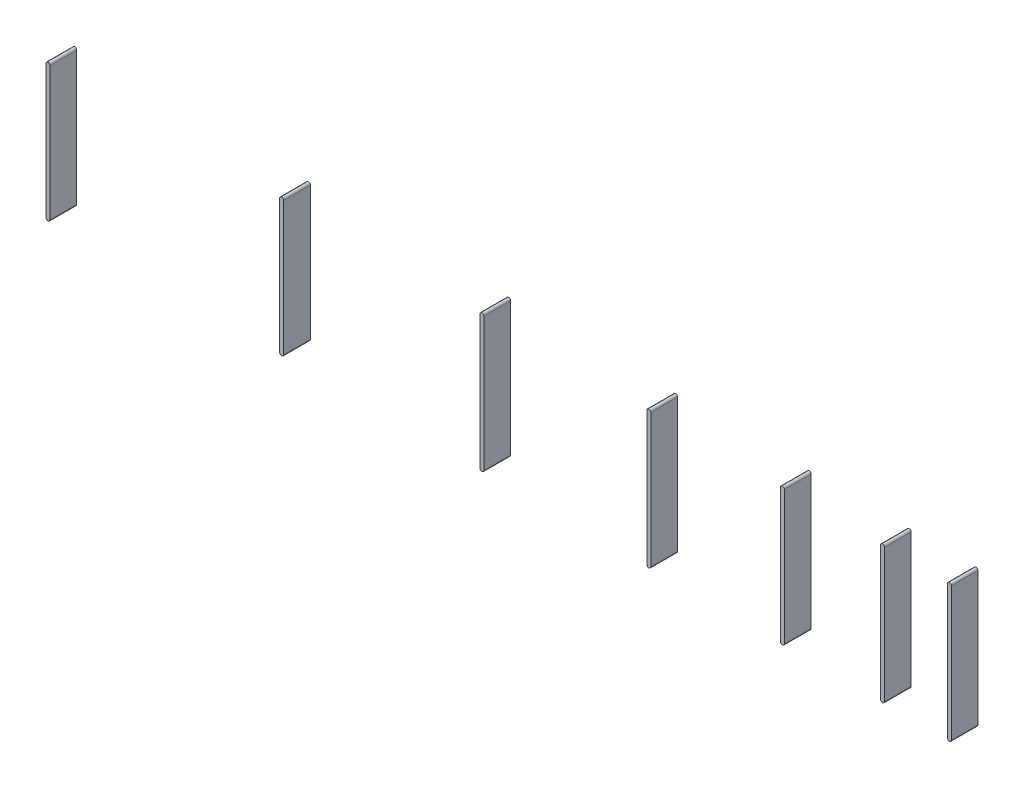
SolidWorks part; units mm, degrees
ref_plane "Front Plane" through (0, 0, 0) normal (0, 0, 1) x (1, 0, 0)
ref_plane "Top Plane" through (0, 0, 0) normal (0, 1, 0) x (1, 0, 0)
ref_plane "Right Plane" through (0, 0, 0) normal (1, 0, 0) x (0, 0, -1)
sketch "Sketch1" plane through (0, 0, 0) normal (0, 0, 1) x (1, 0, 0)
  line L0 (0, 0) -> (0, -20) construction
  line L1 (0.3, 0) -> (0.3, -20)
  line L2 (-0.3, 0) -> (-0.3, -20)
  line L3 (25, 0) -> (25, -20) construction
  line L4 (25.3, 0) -> (25.3, -20)
  line L5 (24.7, 0) -> (24.7, -20)
  line L6 (15, 0) -> (15, -20) construction
  line L7 (15.3, 0) -> (15.3, -20)
  line L8 (14.7, 0) -> (14.7, -20)
  line L9 (-20, 0) -> (-20, -20) construction
  line L10 (-19.7, 0) -> (-19.7, -20)
  line L11 (-20.3, 0) -> (-20.3, -20)
  line L12 (-45, 0) -> (-45, -20) construction
  line L13 (-44.7, 0) -> (-44.7, -20)
  line L14 (-45.3, 0) -> (-45.3, -20)
  line L15 (-75, 0) -> (-75, -20) construction
  line L16 (-74.7, 0) -> (-74.7, -20)
  line L17 (-75.3, 0) -> (-75.3, -20)
  line L18 (-110, 0) -> (-110, -20) construction
  line L19 (-109.7, 0) -> (-109.7, -20)
  line L20 (-110.3, 0) -> (-110.3, -20)
  line L21 (-110, -20) -> (-75, -20) construction
  line L22 (-75, -20) -> (-45, -20) construction
  line L23 (-45, -20) -> (-20, -20) construction
  line L24 (-20, -20) -> (0, -20) construction
  line L25 (0, -20) -> (15, -20) construction
  line L26 (15, -20) -> (25, -20) construction
  line L27 (25.3, -20) -> (30.3, -20) construction
  arc A0 (0.3, 0) -> (-0.3, 0) centre (0, 0) ccw
  arc A1 (-0.3, -20) -> (0.3, -20) centre (0, -20) ccw
  arc A2 (25.3, 0) -> (24.7, 0) centre (25, 0) ccw
  arc A3 (24.7, -20) -> (25.3, -20) centre (25, -20) ccw
  arc A4 (15.3, 0) -> (14.7, 0) centre (15, 0) ccw
  arc A5 (14.7, -20) -> (15.3, -20) centre (15, -20) ccw
  arc A6 (-19.7, 0) -> (-20.3, 0) centre (-20, 0) ccw
  arc A7 (-20.3, -20) -> (-19.7, -20) centre (-20, -20) ccw
  arc A8 (-44.7, 0) -> (-45.3, 0) centre (-45, 0) ccw
  arc A9 (-45.3, -20) -> (-44.7, -20) centre (-45, -20) ccw
  arc A10 (-74.7, 0) -> (-75.3, 0) centre (-75, 0) ccw
  arc A11 (-75.3, -20) -> (-74.7, -20) centre (-75, -20) ccw
  arc A12 (-109.7, 0) -> (-110.3, 0) centre (-110, 0) ccw
  arc A13 (-110.3, -20) -> (-109.7, -20) centre (-110, -20) ccw
  point P3 (0, -10)
  point P10 (25, -10)
  point P17 (15, -10)
  point P24 (-20, -10)
  point P31 (-45, -10)
  point P38 (-75, -10)
  point P45 (-110, -10)
  dimension "D9" = 0.3
  dimension "D2" = 35
  dimension "D1" = 5
  dimension "D3" = 30
  dimension "D4" = 25
  dimension "D5" = 20
  dimension "D6" = 15
  dimension "D7" = 10
  dimension "D8" = 20
extrude "Boss-Extrude1" add sketch "Sketch1" along normal blind 4
equation "\"D4@Sketch1\"=\"D3@Sketch1\"-\"D1@Sketch1\""
equation "\"D5@Sketch1\"=\"D4@Sketch1\"-\"D1@Sketch1\""
equation "\"D6@Sketch1\"=\"D5@Sketch1\"-\"D1@Sketch1\""
equation "\"D7@Sketch1\"=\"D6@Sketch1\"-\"D1@Sketch1\""
equation "\"D3@Sketch1\"=\"D2@Sketch1\"-\"D1@Sketch1\""
